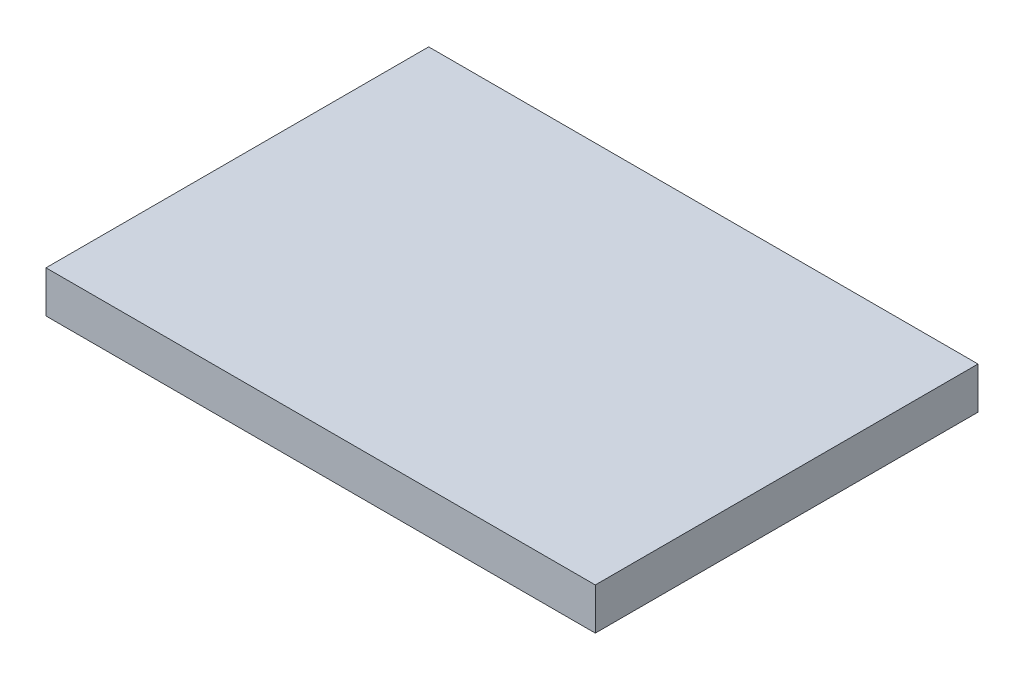
SolidWorks part; units mm, degrees
ref_plane "Front Plane" through (0, 0, 0) normal (0, 0, 1) x (1, 0, 0)
ref_plane "Top Plane" through (0, 0, 0) normal (0, 1, 0) x (1, 0, 0)
ref_plane "Right Plane" through (0, 0, 0) normal (1, 0, 0) x (0, 0, -1)
sketch "Sketch1" plane through (0, 0, 0) normal (0, 1, 0) x (1, 0, 0)
  line L1 (-42.5, 27.5) -> (36.4466, 27.5)
  line L2 (-42.5, 27.5) -> (-42.5, -27.5)
  line L3 (-42.5, -27.5) -> (36.4466, -27.5)
  line L4 (36.4466, 27.5) -> (36.4466, -27.5)
extrude "Boss-Extrude1" add sketch "Sketch1" along normal blind 6
